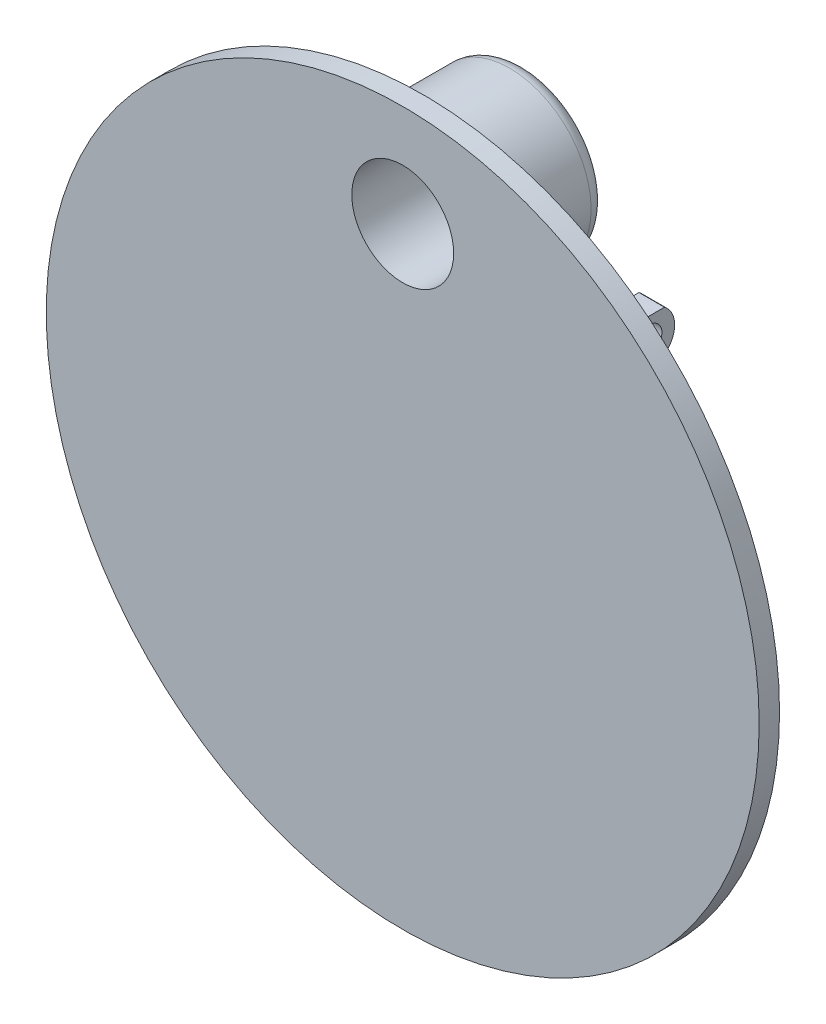
SolidWorks part; units mm, degrees
ref_plane "Front Plane" through (0, 0, 0) normal (0, 0, 1) x (1, 0, 0)
ref_plane "Top Plane" through (0, 0, 0) normal (0, 1, 0) x (1, 0, 0)
ref_plane "Right Plane" through (0, 0, 0) normal (1, 0, 0) x (0, 0, -1)
sketch "Sketch1" plane through (0, 0, 0) normal (0, 0, 1) x (1, 0, 0)
  circle A0 centre (0, 0) radius 35
  dimension "D1" = 70
extrude "Boss-Extrude1" add sketch "Sketch1" along normal blind 2
sketch "Sketch2" plane through (0, 0, 2) normal (0, 0, 1) x (1, 0, 0)
  circle A0 centre (0, 25) radius 5
  dimension "D1" = 10
  dimension "D2" = 25
extrude "Cut-Extrude2" cut sketch "Sketch2" against normal up to vertex (2 mm away) up to point (0, 0, 0)
sketch "Sketch4" plane through (0, 0, 0) normal (0, 0, -1) x (-1, 0, 0)
  circle A0 centre (0, 25) radius 5
  circle A1 centre (0, 25) radius 8
  dimension "D2" = 10
  dimension "D3" = 16
  dimension "D1" = 25
extrude "Boss-Extrude3" add sketch "Sketch4" along normal blind 10
fillet "Fillet3" radius 0.75 1 edges at (-5, 25, -10)
fillet "Fillet4" radius 1.5 1 edges at (-8, 25, -10)
sketch "Sketch5" plane through (8, 0, 0) normal (1, 0, 0) x (0, 0, -1)
  line L0 (13, 15.7692) -> (0, 15.7692)
  line L6 (0, 15.7692) -> (0, 11.7692)
  line L7 (0, 11.7692) -> (10, 11.7692)
  line L11 (10, 19.7692) -> (13, 19.7692) construction
  line L12 (0, -35) -> (0, 35) construction
  arc A0 (13, 15.7692) -> (10, 11.7692) centre (11.5, 13.7692) cw
  point P5 (0, 11.7692)
  dimension "D2" = 2.5
  dimension "D1" = 4
  dimension "D3" = 6
  dimension "D4" = 13
  dimension "D5" = 11.5
  dimension "D6" = 11.5
extrude "Boss-Extrude4" add sketch "Sketch5" along normal blind 2.5 from offset 0.2
sketch "Sketch6" plane through (-8, 0, 0) normal (-1, 0, 0) x (0, 0, 1)
  line L0 (-10, 11.7692) -> (0, 11.7692)
  line L1 (0, 11.7692) -> (0, 15.7692)
  line L2 (0, 15.7692) -> (-13, 15.7692)
  arc A1 (-13, 15.7692) -> (-10, 11.7692) centre (-11.5, 13.7692) ccw
  dimension "D1" = 11.5
  dimension "D2" = 2.5
  dimension "D3" = 13
extrude "Boss-Extrude5" add sketch "Sketch6" along normal blind 2.5 from offset 0.2
sketch "Sketch7" plane through (-10.7, 0, 0) normal (-1, 0, 0) x (0, 0, 1)
  circle A0 centre (-11.5, 13.7692) radius 1.25
  dimension "D1" = 2.5
extrude "Cut-Extrude3" cut sketch "Sketch7" against normal through all
